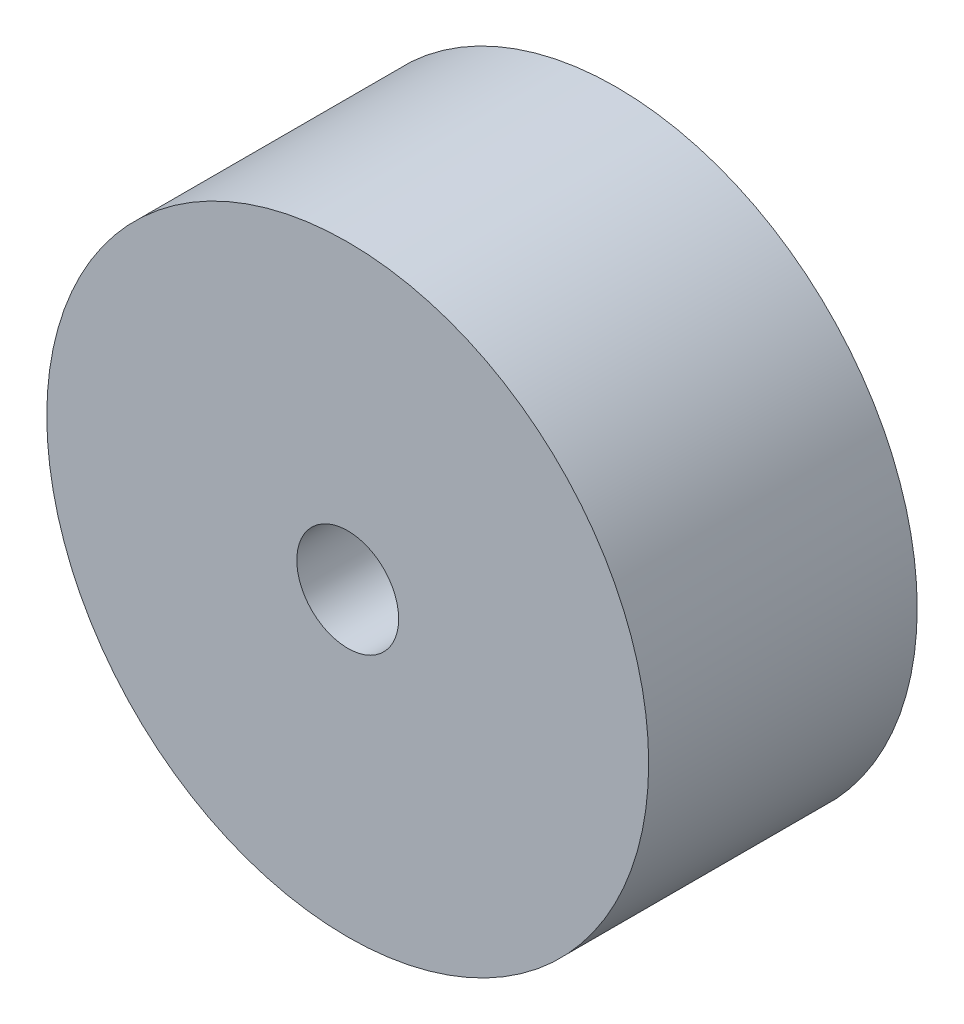
SolidWorks part; units mm, degrees
ref_plane "Front Plane" through (0, 0, 0) normal (0, 0, 1) x (1, 0, 0)
ref_plane "Top Plane" through (0, 0, 0) normal (0, 1, 0) x (1, 0, 0)
ref_plane "Right Plane" through (0, 0, 0) normal (1, 0, 0) x (0, 0, -1)
sketch "Sketch1" plane through (0, 0, 0) normal (0, 0, 1) x (1, 0, 0)
  circle A0 centre (-29.0823, -1.7038) radius 6.5
  dimension "D1" = 13
extrude "Boss-Extrude1" add sketch "Sketch1" along normal blind 5.8
sketch "Sketch2" plane through (0, 0, 0) normal (0, 0, -1) x (-1, 0, 0)
  circle A0 centre (29.0823, -1.7038) radius 4.8
  dimension "D1" = 9.6
extrude "Cut-Extrude1" cut sketch "Sketch2" against normal blind 1.5875
sketch "Sketch3" plane through (0, 0, 1.5875) normal (0, 0, -1) x (-1, 0, 0)
  circle A0 centre (29.0823, -1.7038) radius 1
  dimension "D1" = 2
extrude "Boss-Extrude2" add sketch "Sketch3" along normal blind 1.5875
sketch "Sketch4" plane through (0, 0, 0) normal (0, 0, -1) x (-1, 0, 0)
  circle A0 centre (29.0823, -1.7038) radius 1.525
  dimension "D1" = 3.05
extrude "Boss-Extrude3" add sketch "Sketch4" against normal blind 3
sketch "Sketch5" plane through (0, 0, 0) normal (0, 0, -1) x (-1, 0, 0)
  circle A0 centre (29.0823, -1.7038) radius 0.85
  dimension "D1" = 1.7
extrude "Cut-Extrude2" cut sketch "Sketch5" against normal through all
sketch "Sketch6" plane through (0, 0, 5.8) normal (0, 0, 1) x (1, 0, 0)
  circle A0 centre (-29.0823, -1.7038) radius 1.1
  dimension "D1" = 2.2
extrude "Cut-Extrude3" cut sketch "Sketch6" against normal blind 3
fillet "Fillet1" radius 0.2 1 edges at (-30.6073, -1.7038, 0)
